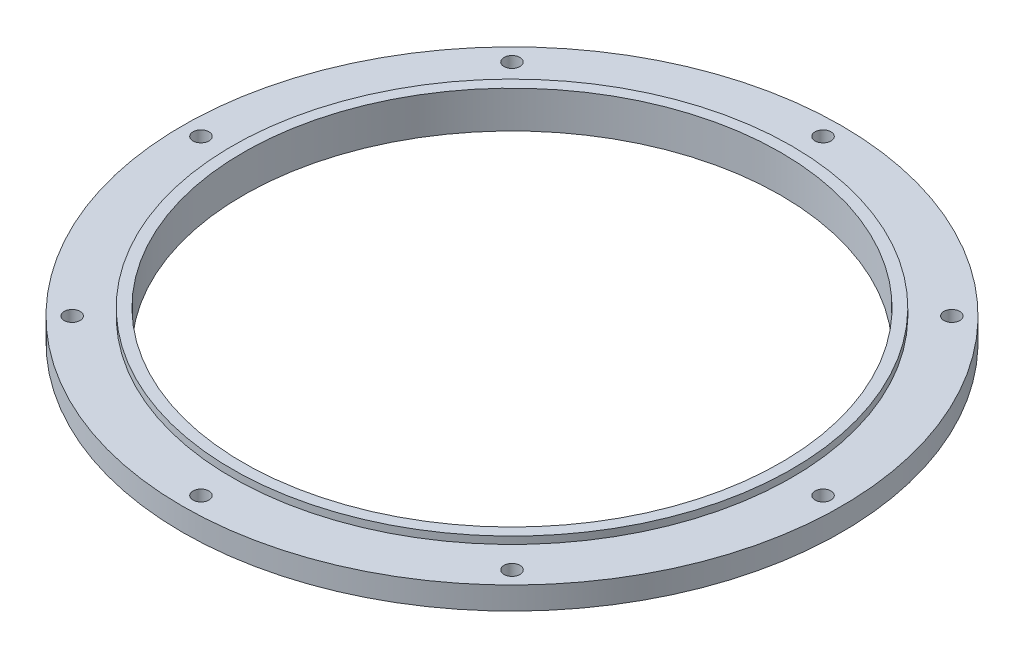
SolidWorks part; units mm, degrees
ref_plane "前视基准面" through (0, 0, 0) normal (0, 0, 1) x (1, 0, 0)
ref_plane "上视基准面" through (0, 0, 0) normal (0, 1, 0) x (1, 0, 0)
ref_plane "右视基准面" through (0, 0, 0) normal (1, 0, 0) x (0, 0, -1)
other "Configuration Table"
sketch "草图1" plane through (0, 0, 0) normal (0, 0, 1) x (1, 0, 0)
  line L0 (0, 0) -> (0, 30.9262) construction
  line L2 (75.5, 0) -> (88.9, 0)
  line L4 (75.5, 6.1) -> (88.9, 6.1)
  line L5 (88.9, 0) -> (88.9, 6.1)
  line L6 (72.5, 8.05) -> (75.5, 8.05)
  line L7 (75.5, 8.05) -> (75.5, 6.1)
  line L9 (72.5, -1.95) -> (75.5, -1.95)
  line L10 (75.5, -1.95) -> (75.5, 0)
  line L11 (72.5, 8.05) -> (72.5, -1.95)
  dimension "D1" = 88.9
  dimension "D2" = 151
  dimension "D3" = 6.1
  dimension "D5" = 3
  dimension "D6" = 10
revolve "旋转1" add sketch "草图1" angle 360 about L0
sketch "草图2" plane through (0, 6.1, 0) normal (0, 1, 0) x (1, 0, 0)
  circle A0 centre (0, 0) radius 83.9 construction
  circle A2 centre (-83.9, 0) radius 2.15
  circle A4 centre (-59.3263, 59.3263) radius 2.15
  circle A5 centre (0, 83.9) radius 2.15
  circle A6 centre (59.3263, 59.3263) radius 2.15
  circle A7 centre (83.9, 0) radius 2.15
  circle A8 centre (59.3263, -59.3263) radius 2.15
  circle A9 centre (0, -83.9) radius 2.15
  circle A10 centre (-59.3263, -59.3263) radius 2.15
  point P24 (0, 0)
  dimension "D1" = 167.8
  dimension "D2" = 4.3
  dimension "D3" = 8
extrude "切除-拉伸1" cut sketch "草图2" against normal blind 10
